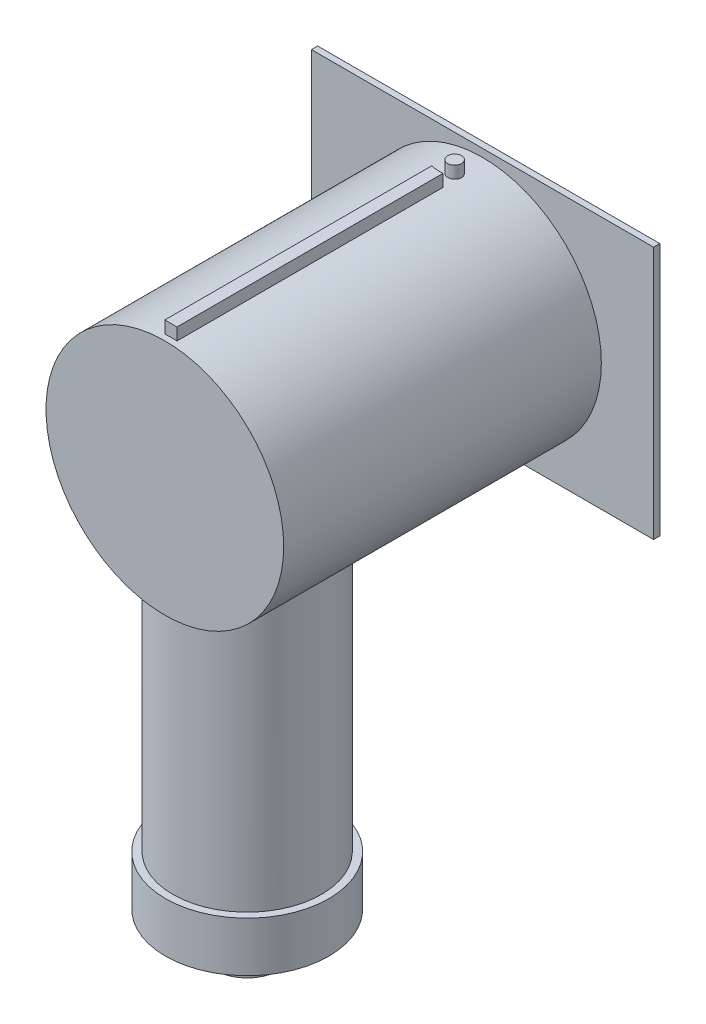
SolidWorks part; units mm, degrees
ref_plane "Front Plane" through (0, 0, 0) normal (0, 0, 1) x (1, 0, 0)
ref_plane "Top Plane" through (0, 0, 0) normal (0, 1, 0) x (1, 0, 0)
ref_plane "Right Plane" through (0, 0, 0) normal (1, 0, 0) x (0, 0, -1)
sketch "Sketch2" plane through (0, 0, 0) normal (0, 0, 1) x (1, 0, 0)
  line L1 (27.4654, -20.328) -> (-27.4654, -20.328)
  line L2 (27.4654, -20.328) -> (27.4654, 20.328)
  line L3 (27.4654, 20.328) -> (-27.4654, 20.328)
  line L4 (-27.4654, -20.328) -> (-27.4654, 20.328)
  line L5 (27.4654, -20.328) -> (-27.4654, 20.328) construction
  line L6 (27.4654, 20.328) -> (-27.4654, -20.328) construction
  point P0 (0, 0)
extrude "Boss-Extrude1" add sketch "Sketch2" along normal blind 1
sketch "Sketch3" plane through (0, 0, 1) normal (0, 0, 1) x (1, 0, 0)
  circle A0 centre (0, 0) radius 19.0761
extrude "Boss-Extrude2" add sketch "Sketch3" along normal blind 51
ref_plane "Plane1" through (0, -19, 0) normal (0, 1, 0) x (1, 0, 0)
sketch "Sketch4" plane through (0, -19, 0) normal (0, 1, 0) x (1, 0, 0)
  circle A0 centre (-0.4555, -38.3266) radius 11.934
extrude "Boss-Extrude3" add sketch "Sketch4" against normal blind 40
sketch "Sketch5" plane through (0, -19, 0) normal (0, 1, 0) x (1, 0, 0)
  circle A0 centre (-0.4555, -38.3266) radius 11.934
extrude "Boss-Extrude4" add sketch "Sketch5" along normal blind 10
sketch "Sketch6" plane through (0, -59, 0) normal (0, -1, 0) x (1, 0, 0)
  circle A0 centre (-0.4555, 38.3266) radius 13.1123
extrude "Boss-Extrude5" add sketch "Sketch6" along normal blind 8
sketch "Sketch7" plane through (0, -67, 0) normal (0, -1, 0) x (1, 0, 0)
  circle A0 centre (-0.4555, 38.3266) radius 5.0711
extrude "Boss-Extrude6" add sketch "Sketch7" along normal blind 6
ref_plane "Plane2" through (0, 19, 0) normal (0, 1, 0) x (1, 0, 0)
sketch "Sketch8" plane through (0, 19, 0) normal (0, 1, 0) x (1, 0, 0)
  line L1 (0.977, 34.7289) -> (-0.977, 34.7289)
  line L2 (0.977, -8.3246) -> (0.977, -51.0317)
  line L3 (0.977, -51.0317) -> (-0.977, -51.0317)
  line L4 (-0.977, -8.1514) -> (-0.977, -51.0317)
  circle A1 centre (0, -5.4744) radius 1.1074
  spline S0 degree 2 poles (-0.977, -8.1514) (-0.0151, -8.4099) (0.977, -8.3246) knots 0 0 0 1 1 1
extrude "Boss-Extrude7" add sketch "Sketch8" along normal blind 2 contours S0 L4 L3 L2 | A1
scale "Scale1" scale about origin uniform scaling yes scale factor 0.5
scale "Scale2" scale about origin uniform scaling yes scale factor 0.5
scale "Scale3" scale about origin uniform scaling yes scale factor 0.5
